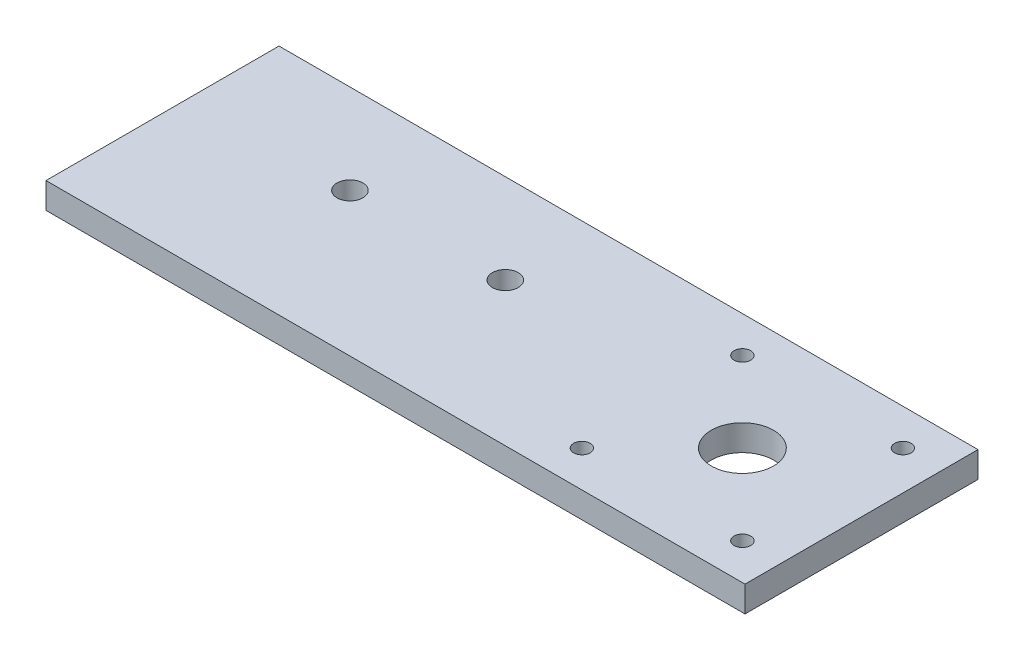
SolidWorks part; units mm, degrees
ref_plane "Front" through (0, 0, 0) normal (0, 0, 1) x (1, 0, 0)
ref_plane "Top" through (0, 0, 0) normal (0, 1, 0) x (1, 0, 0)
ref_plane "Right" through (0, 0, 0) normal (1, 0, 0) x (0, 0, -1)
sketch "Sketch1" plane through (0, 0, 0) normal (0, 1, 0) x (1, 0, 0)
  line L1 (-67.5, 22.5) -> (67.5, 22.5)
  line L2 (-67.5, 22.5) -> (-67.5, -22.5)
  line L3 (-67.5, -22.5) -> (67.5, -22.5)
  line L4 (67.5, 22.5) -> (67.5, -22.5)
  line L5 (-67.5, 22.5) -> (67.5, -22.5) construction
  line L6 (-67.5, -22.5) -> (67.5, 22.5) construction
  point P0 (0, 0)
  dimension "D1" = 135
  dimension "D2" = 45
extrude "Boss-Extrude1" add sketch "Sketch1" along normal blind 5
sketch "Sketch3" plane through (0, 0, 0) normal (0, -1, 0) x (1, 0, 0)
  circle A0 centre (-36.4987, -5.1987) radius 2.5
  circle A1 centre (-6.4962, -5.1987) radius 2.5
  dimension "D1" = 5
extrude "Cut-Extrude2" cut sketch "Sketch3" against normal up to next
sketch "Sketch4" plane through (0, 0, 0) normal (0, -1, 0) x (1, 0, 0)
  circle A0 centre (44.5, 0.0025) radius 6
  circle A1 centre (60, 15.5025) radius 1.6
  circle A2 centre (29, 15.5025) radius 1.6
  circle A3 centre (29, -15.4975) radius 1.6
  circle A4 centre (60, -15.4975) radius 1.6
  dimension "D1" = 12
  dimension "D2" = 3.2
extrude "Cut-Extrude3" cut sketch "Sketch4" against normal through all
